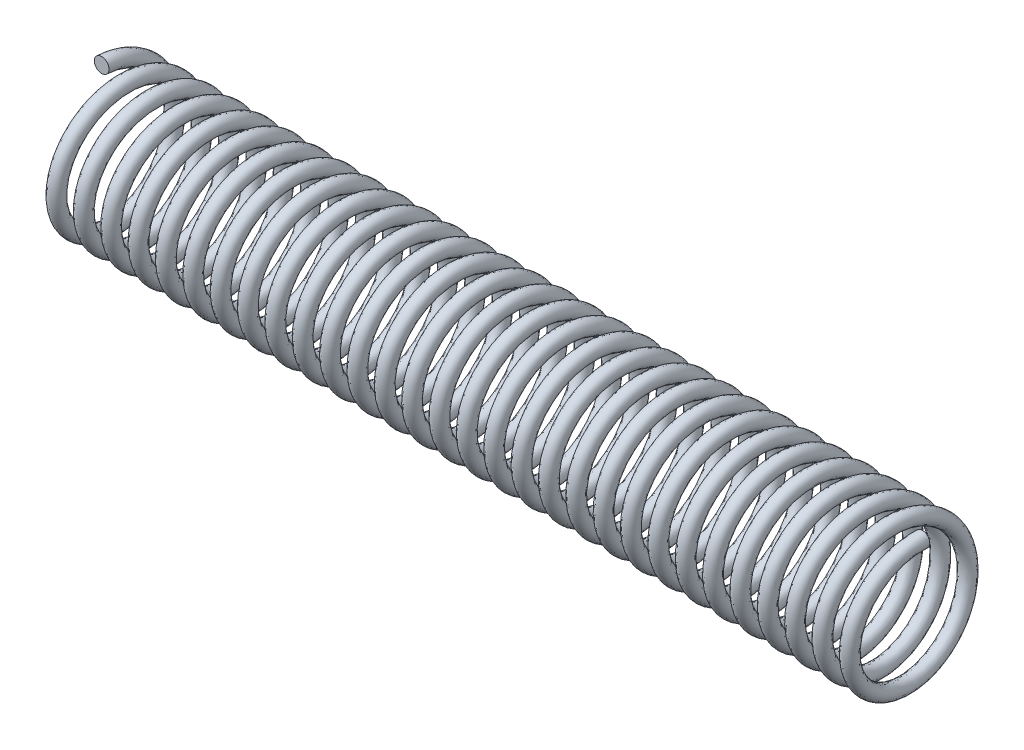
SolidWorks part; units mm, degrees
material "AISI 316 Stainless Steel Sheet (SS)"
ref_plane "Front Plane" through (0, 0, 0) normal (0, 0, 1) x (1, 0, 0)
ref_plane "Top Plane" through (0, 0, 0) normal (0, 1, 0) x (1, 0, 0)
ref_plane "Right Plane" through (0, 0, 0) normal (1, 0, 0) x (0, 0, -1)
sketch "Sketch1" plane through (0, 0, 0) normal (1, 0, 0) x (0, 0, -1)
  circle A0 centre (0, 0) radius 3.9624
  dimension "D1" = 7.9248
curve "Helix/Spiral1" pitch 1.651 height 49.53 turns 30
sketch "Sketch2" plane through (0, 0, 0) normal (0, 0, 1) x (1, 0, 0)
  circle A0 centre (0, 3.9624) radius 0.4445
  spline S0 degree 3 poles (0, 3.9624) (0.0342, 3.9624) (0.1033, 3.7561) (0.2063, 2.8748) (0.3096, 1.5558) (0.4127, 0) (0.5159, -1.5558) (0.6191, -2.8748) (0.7223, -3.7561) (0.8255, -4.0656) (0.9287, -3.7561) (1.0319, -2.8748) (1.1351, -1.5558) (1.2382, 0) (1.3414, 1.5558) (1.4446, 2.8748) (1.5478, 3.7561) (1.651, 4.0656) (1.7542, 3.7561) (1.8574, 2.8748) (1.9606, 1.5558) (2.0637, 0) (2.1669, -1.5558) (2.2701, -2.8748) (2.3733, -3.7561) (2.4765, -4.0656) (2.5797, -3.7561) (2.6829, -2.8748) (2.7861, -1.5558) (2.8892, 0) (2.9924, 1.5558) (3.0956, 2.8748) (3.1988, 3.7561) (3.302, 4.0656) (3.4052, 3.7561) (3.5084, 2.8748) (3.6116, 1.5558) (3.7147, 0) (3.8179, -1.5558) (3.9211, -2.8748) (4.0243, -3.7561) (4.1275, -4.0656) (4.2307, -3.7561) (4.3339, -2.8748) (4.4371, -1.5558) (4.5403, 0) (4.6434, 1.5558) (4.7466, 2.8748) (4.8498, 3.7561) (4.953, 4.0656) (5.0562, 3.7561) (5.1594, 2.8748) (5.2626, 1.5558) (5.3658, 0) (5.4689, -1.5558) (5.5721, -2.8748) (5.6753, -3.7561) (5.7785, -4.0656) (5.8817, -3.7561) (5.9849, -2.8748) (6.0881, -1.5558) (6.1913, 0) (6.2944, 1.5558) (6.3976, 2.8748) (6.5008, 3.7561) (6.604, 4.0656) (6.7072, 3.7561) (6.8104, 2.8748) (6.9136, 1.5558) (7.0168, 0) (7.1199, -1.5558) (7.2231, -2.8748) (7.3263, -3.7561) (7.4295, -4.0656) (7.5327, -3.7561) (7.6359, -2.8748) (7.7391, -1.5558) (7.8423, 0) (7.9454, 1.5558) (8.0486, 2.8748) (8.1518, 3.7561) (8.255, 4.0656) (8.3582, 3.7561) (8.4614, 2.8748) (8.5646, 1.5558) (8.6678, 0) (8.7709, -1.5558) (8.8741, -2.8748) (8.9773, -3.7561) (9.0805, -4.0656) (9.1837, -3.7561) (9.2869, -2.8748) (9.3901, -1.5558) (9.4933, 0) (9.5964, 1.5558) (9.6996, 2.8748) (9.8028, 3.7561) (9.906, 4.0656) (10.0092, 3.7561) (10.1124, 2.8748) (10.2156, 1.5558) (10.3188, 0) (10.4219, -1.5558) (10.5251, -2.8748) (10.6283, -3.7561) (10.7315, -4.0656) (10.8347, -3.7561) (10.9379, -2.8748) (11.0411, -1.5558) (11.1443, 0) (11.2474, 1.5558) (11.3506, 2.8748) (11.4538, 3.7561) (11.557, 4.0656) (11.6602, 3.7561) (11.7634, 2.8748) (11.8666, 1.5558) (11.9698, 0) (12.0729, -1.5558) (12.1761, -2.8748) (12.2793, -3.7561) (12.3825, -4.0656) (12.4857, -3.7561) (12.5889, -2.8748) (12.6921, -1.5558) (12.7953, 0) (12.8984, 1.5558) (13.0016, 2.8748) (13.1048, 3.7561) (13.208, 4.0656) (13.3112, 3.7561) (13.4144, 2.8748) (13.5176, 1.5558) (13.6208, 0) (13.7239, -1.5558) (13.8271, -2.8748) (13.9303, -3.7561) (14.0335, -4.0656) (14.1367, -3.7561) (14.2399, -2.8748) (14.3431, -1.5558) (14.4463, 0) (14.5494, 1.5558) (14.6526, 2.8748) (14.7558, 3.7561) (14.859, 4.0656) (14.9622, 3.7561) (15.0654, 2.8748) (15.1686, 1.5558) (15.2718, 0) (15.3749, -1.5558) (15.4781, -2.8748) (15.5813, -3.7561) (15.6845, -4.0656) (15.7877, -3.7561) (15.8909, -2.8748) (15.9941, -1.5558) (16.0973, 0) (16.2004, 1.5558) (16.3036, 2.8748) (16.4068, 3.7561) (16.51, 4.0656) (16.6132, 3.7561) (16.7164, 2.8748) (16.8196, 1.5558) (16.9228, 0) (17.0259, -1.5558) (17.1291, -2.8748) (17.2323, -3.7561) (17.3355, -4.0656) (17.4387, -3.7561) (17.5419, -2.8748) (17.6451, -1.5558) (17.7483, 0) (17.8514, 1.5558) (17.9546, 2.8748) (18.0578, 3.7561) (18.161, 4.0656) (18.2642, 3.7561) (18.3674, 2.8748) (18.4706, 1.5558) (18.5738, 0) (18.6769, -1.5558) (18.7801, -2.8748) (18.8833, -3.7561) (18.9865, -4.0656) (19.0897, -3.7561) (19.1929, -2.8748) (19.2961, -1.5558) (19.3993, 0) (19.5024, 1.5558) (19.6056, 2.8748) (19.7088, 3.7561) (19.812, 4.0656) (19.9152, 3.7561) (20.0184, 2.8748) (20.1216, 1.5558) (20.2248, 0) (20.3279, -1.5558) (20.4311, -2.8748) (20.5343, -3.7561) (20.6375, -4.0656) (20.7407, -3.7561) (20.8439, -2.8748) (20.9471, -1.5558) (21.0503, 0) (21.1534, 1.5558) (21.2566, 2.8748) (21.3598, 3.7561) (21.463, 4.0656) (21.5662, 3.7561) (21.6694, 2.8748) (21.7726, 1.5558) (21.8758, 0) (21.9789, -1.5558) (22.0821, -2.8748) (22.1853, -3.7561) (22.2885, -4.0656) (22.3917, -3.7561) (22.4949, -2.8748) (22.5981, -1.5558) (22.7013, 0) (22.8044, 1.5558) (22.9076, 2.8748) (23.0108, 3.7561) (23.114, 4.0656) (23.2172, 3.7561) (23.3204, 2.8748) (23.4236, 1.5558) (23.5268, 0) (23.6299, -1.5558) (23.7331, -2.8748) (23.8363, -3.7561) (23.9395, -4.0656) (24.0427, -3.7561) (24.1459, -2.8748) (24.2491, -1.5558) (24.3523, 0) (24.4554, 1.5558) (24.5586, 2.8748) (24.6618, 3.7561) (24.765, 4.0656) (24.8682, 3.7561) (24.9714, 2.8748) (25.0746, 1.5558) (25.1778, 0) (25.2809, -1.5558) (25.3841, -2.8748) (25.4873, -3.7561) (25.5905, -4.0656) (25.6937, -3.7561) (25.7969, -2.8748) (25.9001, -1.5558) (26.0033, 0) (26.1064, 1.5558) (26.2096, 2.8748) (26.3128, 3.7561) (26.416, 4.0656) (26.5192, 3.7561) (26.6224, 2.8748) (26.7256, 1.5558) (26.8288, 0) (26.9319, -1.5558) (27.0351, -2.8748) (27.1383, -3.7561) (27.2415, -4.0656) (27.3447, -3.7561) (27.4479, -2.8748) (27.5511, -1.5558) (27.6543, 0) (27.7574, 1.5558) (27.8606, 2.8748) (27.9638, 3.7561) (28.067, 4.0656) (28.1702, 3.7561) (28.2734, 2.8748) (28.3766, 1.5558) (28.4798, 0) (28.5829, -1.5558) (28.6861, -2.8748) (28.7893, -3.7561) (28.8925, -4.0656) (28.9957, -3.7561) (29.0989, -2.8748) (29.2021, -1.5558) (29.3053, 0) (29.4084, 1.5558) (29.5116, 2.8748) (29.6148, 3.7561) (29.718, 4.0656) (29.8212, 3.7561) (29.9244, 2.8748) (30.0276, 1.5558) (30.1308, 0) (30.2339, -1.5558) (30.3371, -2.8748) (30.4403, -3.7561) (30.5435, -4.0656) (30.6467, -3.7561) (30.7499, -2.8748) (30.8531, -1.5558) (30.9563, 0) (31.0594, 1.5558) (31.1626, 2.8748) (31.2658, 3.7561) (31.369, 4.0656) (31.4722, 3.7561) (31.5754, 2.8748) (31.6786, 1.5558) (31.7818, 0) (31.8849, -1.5558) (31.9881, -2.8748) (32.0913, -3.7561) (32.1945, -4.0656) (32.2977, -3.7561) (32.4009, -2.8748) (32.5041, -1.5558) (32.6073, 0) (32.7104, 1.5558) (32.8136, 2.8748) (32.9168, 3.7561) (33.02, 4.0656) (33.1232, 3.7561) (33.2264, 2.8748) (33.3296, 1.5558) (33.4328, 0) (33.5359, -1.5558) (33.6391, -2.8748) (33.7423, -3.7561) (33.8455, -4.0656) (33.9487, -3.7561) (34.0519, -2.8748) (34.1551, -1.5558) (34.2583, 0) (34.3614, 1.5558) (34.4646, 2.8748) (34.5678, 3.7561) (34.671, 4.0656) (34.7742, 3.7561) (34.8774, 2.8748) (34.9806, 1.5558) (35.0838, 0) (35.1869, -1.5558) (35.2901, -2.8748) (35.3933, -3.7561) (35.4965, -4.0656) (35.5997, -3.7561) (35.7029, -2.8748) (35.8061, -1.5558) (35.9093, 0) (36.0124, 1.5558) (36.1156, 2.8748) (36.2188, 3.7561) (36.322, 4.0656) (36.4252, 3.7561) (36.5284, 2.8748) (36.6316, 1.5558) (36.7348, 0) (36.8379, -1.5558) (36.9411, -2.8748) (37.0443, -3.7561) (37.1475, -4.0656) (37.2507, -3.7561) (37.3539, -2.8748) (37.4571, -1.5558) (37.5603, 0) (37.6634, 1.5558) (37.7666, 2.8748) (37.8698, 3.7561) (37.973, 4.0656) (38.0762, 3.7561) (38.1794, 2.8748) (38.2826, 1.5558) (38.3858, 0) (38.4889, -1.5558) (38.5921, -2.8748) (38.6953, -3.7561) (38.7985, -4.0656) (38.9017, -3.7561) (39.0049, -2.8748) (39.1081, -1.5558) (39.2112, 0) (39.3144, 1.5558) (39.4176, 2.8748) (39.5208, 3.7561) (39.624, 4.0656) (39.7272, 3.7561) (39.8304, 2.8748) (39.9336, 1.5558) (40.0367, 0) (40.1399, -1.5558) (40.2431, -2.8748) (40.3463, -3.7561) (40.4495, -4.0656) (40.5527, -3.7561) (40.6559, -2.8748) (40.7591, -1.5558) (40.8622, 0) (40.9654, 1.5558) (41.0686, 2.8748) (41.1718, 3.7561) (41.275, 4.0656) (41.3782, 3.7561) (41.4814, 2.8748) (41.5846, 1.5558) (41.6877, 0) (41.7909, -1.5558) (41.8941, -2.8748) (41.9973, -3.7561) (42.1005, -4.0656) (42.2037, -3.7561) (42.3069, -2.8748) (42.4101, -1.5558) (42.5132, 0) (42.6164, 1.5558) (42.7196, 2.8748) (42.8228, 3.7561) (42.926, 4.0656) (43.0292, 3.7561) (43.1324, 2.8748) (43.2356, 1.5558) (43.3387, 0) (43.4419, -1.5558) (43.5451, -2.8748) (43.6483, -3.7561) (43.7515, -4.0656) (43.8547, -3.7561) (43.9579, -2.8748) (44.0611, -1.5558) (44.1642, 0) (44.2674, 1.5558) (44.3706, 2.8748) (44.4738, 3.7561) (44.577, 4.0656) (44.6802, 3.7561) (44.7834, 2.8748) (44.8866, 1.5558) (44.9897, 0) (45.0929, -1.5558) (45.1961, -2.8748) (45.2993, -3.7561) (45.4025, -4.0656) (45.5057, -3.7561) (45.6089, -2.8748) (45.7121, -1.5558) (45.8152, 0) (45.9184, 1.5558) (46.0216, 2.8748) (46.1248, 3.7561) (46.228, 4.0656) (46.3312, 3.7561) (46.4344, 2.8748) (46.5376, 1.5558) (46.6407, 0) (46.7439, -1.5558) (46.8471, -2.8748) (46.9503, -3.7561) (47.0535, -4.0656) (47.1567, -3.7561) (47.2599, -2.8748) (47.3631, -1.5558) (47.4662, 0) (47.5694, 1.5558) (47.6726, 2.8748) (47.7758, 3.7561) (47.879, 4.0656) (47.9822, 3.7561) (48.0854, 2.8748) (48.1886, 1.5558) (48.2918, 0) (48.3949, -1.5558) (48.4981, -2.8748) (48.6013, -3.7561) (48.7045, -4.0656) (48.8077, -3.7561) (48.9109, -2.8748) (49.0141, -1.5558) (49.1173, 0) (49.2204, 1.5558) (49.3237, 2.8748) (49.4267, 3.7561) (49.4958, 3.9624) (49.53, 3.9624) knots 0 0 0 0 0.002083 0.004167 0.00625 0.008333 0.010417 0.0125 0.014583 0.016667 0.01875 0.020833 0.022917 0.025 0.027083 0.029167 0.03125 0.033333 0.035417 0.0375 0.039583 0.041667 0.04375 0.045833 0.047917 0.05 0.052083 0.054167 0.05625 0.058333 0.060417 0.0625 0.064583 0.066667 0.06875 0.070833 0.072917 0.075 0.077083 0.079167 0.08125 0.083333 0.085417 0.0875 0.089583 0.091667 0.09375 0.095833 0.097917 0.1 0.102083 0.104167 0.10625 0.108333 0.110417 0.1125 0.114583 0.116667 0.11875 0.120833 0.122917 0.125 0.127083 0.129167 0.13125 0.133333 0.135417 0.1375 0.139583 0.141667 0.14375 0.145833 0.147917 0.15 0.152083 0.154167 0.15625 0.158333 0.160417 0.1625 0.164583 0.166667 0.16875 0.170833 0.172917 0.175 0.177083 0.179167 0.18125 0.183333 0.185417 0.1875 0.189583 0.191667 0.19375 0.195833 0.197917 0.2 0.202083 0.204167 0.20625 0.208333 0.210417 0.2125 0.214583 0.216667 0.21875 0.220833 0.222917 0.225 0.227083 0.229167 0.23125 0.233333 0.235417 0.2375 0.239583 0.241667 0.24375 0.245833 0.247917 0.25 0.252083 0.254167 0.25625 0.258333 0.260417 0.2625 0.264583 0.266667 0.26875 0.270833 0.272917 0.275 0.277083 0.279167 0.28125 0.283333 0.285417 0.2875 0.289583 0.291667 0.29375 0.295833 0.297917 0.3 0.302083 0.304167 0.30625 0.308333 0.310417 0.3125 0.314583 0.316667 0.31875 0.320833 0.322917 0.325 0.327083 0.329167 0.33125 0.333333 0.335417 0.3375 0.339583 0.341667 0.34375 0.345833 0.347917 0.35 0.352083 0.354167 0.35625 0.358333 0.360417 0.3625 0.364583 0.366667 0.36875 0.370833 0.372917 0.375 0.377083 0.379167 0.38125 0.383333 0.385417 0.3875 0.389583 0.391667 0.39375 0.395833 0.397917 0.4 0.402083 0.404167 0.40625 0.408333 0.410417 0.4125 0.414583 0.416667 0.41875 0.420833 0.422917 0.425 0.427083 0.429167 0.43125 0.433333 0.435417 0.4375 0.439583 0.441667 0.44375 0.445833 0.447917 0.45 0.452083 0.454167 0.45625 0.458333 0.460417 0.4625 0.464583 0.466667 0.46875 0.470833 0.472917 0.475 0.477083 0.479167 0.48125 0.483333 0.485417 0.4875 0.489583 0.491667 0.49375 0.495833 0.497917 0.5 0.502083 0.504167 0.50625 0.508333 0.510417 0.5125 0.514583 0.516667 0.51875 0.520833 0.522917 0.525 0.527083 0.529167 0.53125 0.533333 0.535417 0.5375 0.539583 0.541667 0.54375 0.545833 0.547917 0.55 0.552083 0.554167 0.55625 0.558333 0.560417 0.5625 0.564583 0.566667 0.56875 0.570833 0.572917 0.575 0.577083 0.579167 0.58125 0.583333 0.585417 0.5875 0.589583 0.591667 0.59375 0.595833 0.597917 0.6 0.602083 0.604167 0.60625 0.608333 0.610417 0.6125 0.614583 0.616667 0.61875 0.620833 0.622917 0.625 0.627083 0.629167 0.63125 0.633333 0.635417 0.6375 0.639583 0.641667 0.64375 0.645833 0.647917 0.65 0.652083 0.654167 0.65625 0.658333 0.660417 0.6625 0.664583 0.666667 0.66875 0.670833 0.672917 0.675 0.677083 0.679167 0.68125 0.683333 0.685417 0.6875 0.689583 0.691667 0.69375 0.695833 0.697917 0.7 0.702083 0.704167 0.70625 0.708333 0.710417 0.7125 0.714583 0.716667 0.71875 0.720833 0.722917 0.725 0.727083 0.729167 0.73125 0.733333 0.735417 0.7375 0.739583 0.741667 0.74375 0.745833 0.747917 0.75 0.752083 0.754167 0.75625 0.758333 0.760417 0.7625 0.764583 0.766667 0.76875 0.770833 0.772917 0.775 0.777083 0.779167 0.78125 0.783333 0.785417 0.7875 0.789583 0.791667 0.79375 0.795833 0.797917 0.8 0.802083 0.804167 0.80625 0.808333 0.810417 0.8125 0.814583 0.816667 0.81875 0.820833 0.822917 0.825 0.827083 0.829167 0.83125 0.833333 0.835417 0.8375 0.839583 0.841667 0.84375 0.845833 0.847917 0.85 0.852083 0.854167 0.85625 0.858333 0.860417 0.8625 0.864583 0.866667 0.86875 0.870833 0.872917 0.875 0.877083 0.879167 0.88125 0.883333 0.885417 0.8875 0.889583 0.891667 0.89375 0.895833 0.897917 0.9 0.902083 0.904167 0.90625 0.908333 0.910417 0.9125 0.914583 0.916667 0.91875 0.920833 0.922917 0.925 0.927083 0.929167 0.93125 0.933333 0.935417 0.9375 0.939583 0.941667 0.94375 0.945833 0.947917 0.95 0.952083 0.954167 0.95625 0.958333 0.960417 0.9625 0.964583 0.966667 0.96875 0.970833 0.972917 0.975 0.977083 0.979167 0.98125 0.983333 0.985417 0.9875 0.989583 0.991667 0.99375 0.995833 0.997917 1 1 1 1 construction
  dimension "D1" = 0.889
sweep "Sweep1" add profiles "Sketch2" path "Helix/Spiral1"
